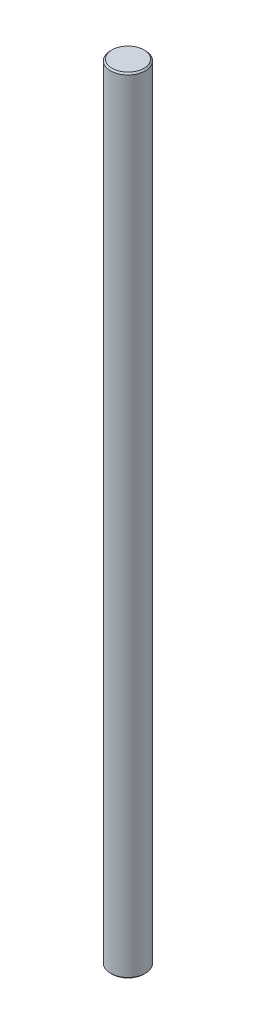
SolidWorks part; units mm, degrees
ref_plane "Front" through (0, 0, 0) normal (0, 0, 1) x (1, 0, 0)
ref_plane "Top" through (0, 0, 0) normal (0, 1, 0) x (1, 0, 0)
ref_plane "Right" through (0, 0, 0) normal (1, 0, 0) x (0, 0, -1)
sketch "Sketch1" plane through (0, 0, 0) normal (0, 1, 0) x (1, 0, 0)
  circle A0 centre (0, 0) radius 6
  dimension "D1" = 12
extrude "Boss-Extrude1" add sketch "Sketch1" along normal blind 270
chamfer "Chamfer1" distance 0.5 angle 45 2 edges at (0, 270, 6) (0, 0, 6)
